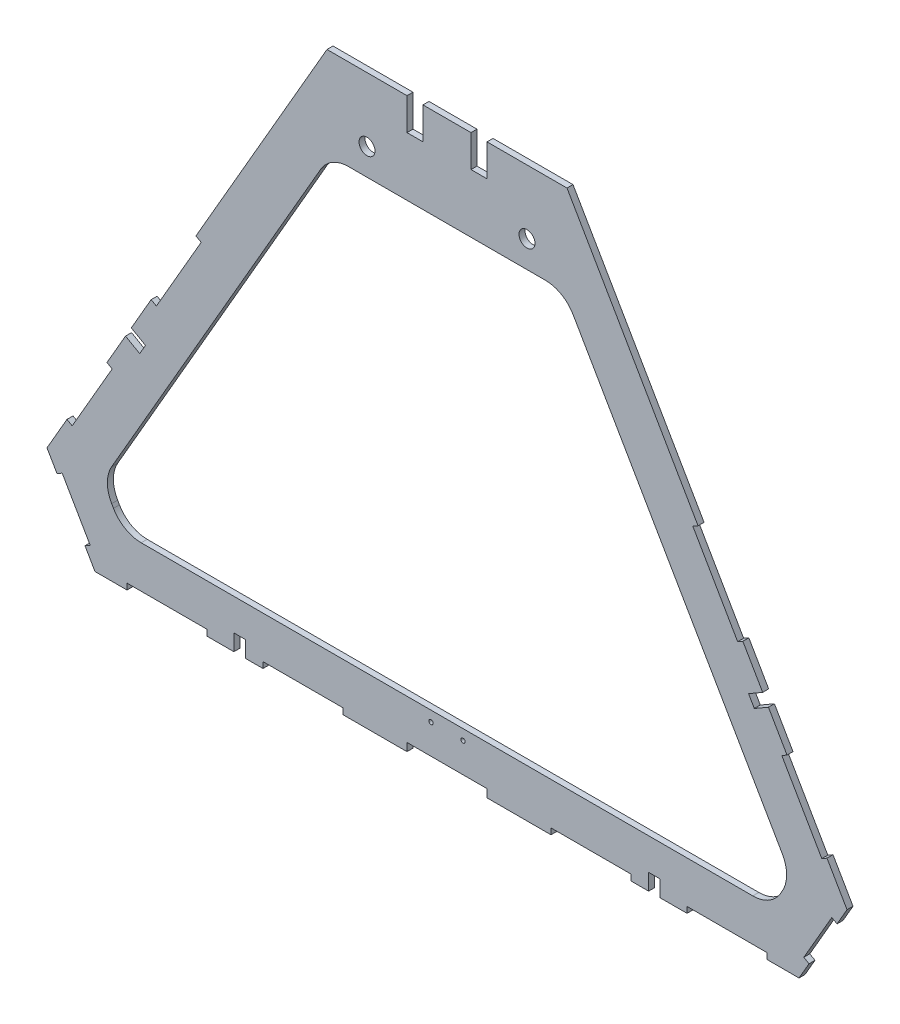
SolidWorks part; units mm, degrees
material "Balsa"
ref_plane "Front Plane" through (0, 0, 0) normal (0, 0, 1) x (1, 0, 0)
ref_plane "Top Plane" through (0, 0, 0) normal (0, 1, 0) x (1, 0, 0)
ref_plane "Right Plane" through (0, 0, 0) normal (1, 0, 0) x (0, 0, -1)
sketch "Sketch1" plane through (0, 0, 0) normal (0, 0, 1) x (1, 0, 0)
  line L0 (-95.25, 450.9394) -> (95.25, 450.9394)
  line L1 (317.5, 65.9911) -> (95.25, 450.9394)
  line L2 (-95.25, 450.9394) -> (-317.5, 65.9911)
  line L3 (-317.5, 65.9911) -> (-279.4, 0)
  line L4 (-279.4, 0) -> (279.4, 0)
  line L5 (279.4, 0) -> (317.5, 65.9911)
  line L6 (0, 0) -> (0, -278.1082) construction
  line L7 (0, 0) -> (435.0174, 0) construction
  point P5 (0, 0)
  point P7 (0, 450.9394)
  dimension "D1" = 558.8
  dimension "D2" = 76.2
  dimension "D3" = 60
  dimension "D4" = 60
  dimension "D5" = 444.5
  dimension "D6" = 60
extrude "Boss-Extrude2" add sketch "Sketch1" along normal blind 4.7625
sketch "Sketch2" plane through (0, 0, 4.7625) normal (0, 0, 1) x (1, 0, 0)
  line L11 (-92.8086, 378.968) -> (92.8086, 378.968)
  line L12 (-279.4, 0) -> (279.4, 0) construction
  line L17 (257.403, 38.1) -> (273.5059, 65.9911)
  line L18 (273.5059, 65.9911) -> (73.253, 412.8394)
  line L19 (73.253, 412.8394) -> (-73.253, 412.8394)
  line L20 (-73.253, 412.8394) -> (-273.5059, 65.9911)
  line L21 (-273.5059, 65.9911) -> (-257.403, 38.1)
  line L25 (-257.403, 38.1) -> (257.403, 38.1)
  line L26 (257.403, 38.1) -> (273.5059, 65.9911)
  line L27 (273.5059, 65.9911) -> (92.8086, 378.968)
  line L29 (-92.8086, 378.968) -> (-273.5059, 65.9911)
  line L30 (-273.5059, 65.9911) -> (-257.403, 38.1)
  line L31 (-257.403, 38.1) -> (257.403, 38.1)
  dimension "D2" = 378.968
  dimension "D1" = 38.1
extrude "Cut-Extrude1" cut sketch "Sketch2" against normal up to next
fillet "Fillet1" radius 25.4 6 edges at (273.5059, 65.9911, 2.3813) (257.403, 38.1, 2.3813) (-257.403, 38.1, 2.3813) (-273.5059, 65.9911, 2.3813) (92.8086, 378.968, 2.3813) (-92.8086, 378.968, 2.3813)
sketch "Sketch3" plane through (0, 0, 4.7625) normal (0, 0, 1) x (1, 0, 0)
  line L0 (0, 450.9394) -> (0, 0) construction
  line L1 (95.25, 450.9394) -> (-95.25, 450.9394) construction
  line L2 (-279.4, 0) -> (279.4, 0) construction
  line L3 (-254, 0) -> (-190.5, 0)
  line L4 (-190.5, 0) -> (-190.5, 4.7625)
  line L5 (-190.5, 4.7625) -> (-254, 4.7625)
  line L6 (-254, 4.7625) -> (-254, 0)
  line L7 (-146.05, 0) -> (-146.05, 4.7625)
  line L8 (-146.05, 4.7625) -> (-82.55, 4.7625)
  line L9 (-82.55, 4.7625) -> (-82.55, 0)
  line L10 (-82.55, 0) -> (-146.05, 0)
  line L11 (-31.75, 0) -> (-31.75, 6.35)
  line L12 (-31.75, 6.35) -> (31.75, 6.35)
  line L14 (31.75, 0) -> (-31.75, 0)
  line L24 (31.75, 0) -> (31.75, 6.35)
  line L33 (-95.25, 450.9394) -> (-317.5, 65.9911) construction
  line L37 (-199.263, 270.7836) -> (-195.1386, 268.4024)
  line L38 (-195.1386, 268.4024) -> (-230.6986, 206.8107)
  line L39 (-230.6986, 206.8107) -> (-234.823, 209.1919)
  line L40 (-234.823, 209.1919) -> (-199.263, 270.7836)
  line L41 (-269.875, 148.4801) -> (-265.7506, 146.0988)
  line L42 (-265.7506, 146.0988) -> (-297.5006, 91.1062)
  line L43 (-297.5006, 91.1062) -> (-301.625, 93.4874)
  line L44 (-301.625, 93.4874) -> (-269.875, 148.4801)
  line L45 (-309.5625, 52.243) -> (-305.4381, 54.6242)
  line L46 (-317.5, 65.9911) -> (-279.4, 0) construction
  line L47 (-305.4381, 54.6242) -> (-283.2131, 16.1294)
  line L48 (-283.2131, 16.1294) -> (-287.3375, 13.7482)
  line L49 (-287.3375, 13.7482) -> (-309.5625, 52.243)
  line L50 (287.3375, 13.7482) -> (309.5625, 52.243)
  line L51 (283.2131, 16.1294) -> (287.3375, 13.7482)
  line L52 (305.4381, 54.6242) -> (283.2131, 16.1294)
  line L53 (309.5625, 52.243) -> (305.4381, 54.6242)
  line L54 (301.625, 93.4874) -> (269.875, 148.4801)
  line L55 (297.5006, 91.1062) -> (301.625, 93.4874)
  line L56 (265.7506, 146.0988) -> (297.5006, 91.1062)
  line L57 (269.875, 148.4801) -> (265.7506, 146.0988)
  line L58 (234.823, 209.1919) -> (199.263, 270.7836)
  line L59 (230.6986, 206.8107) -> (234.823, 209.1919)
  line L60 (195.1386, 268.4024) -> (230.6986, 206.8107)
  line L61 (199.263, 270.7836) -> (195.1386, 268.4024)
  line L62 (82.55, 0) -> (146.05, 0)
  line L63 (82.55, 4.7625) -> (82.55, 0)
  line L64 (146.05, 4.7625) -> (82.55, 4.7625)
  line L65 (146.05, 0) -> (146.05, 4.7625)
  line L66 (254, 4.7625) -> (254, 0)
  line L67 (190.5, 4.7625) -> (254, 4.7625)
  line L68 (190.5, 0) -> (190.5, 4.7625)
  line L69 (254, 0) -> (190.5, 0)
  line L70 (-31.75, 450.9394) -> (-31.75, 425.5394)
  line L71 (-31.75, 425.5394) -> (-19.05, 425.5394)
  line L72 (-19.05, 425.5394) -> (-19.05, 450.9394)
  line L73 (-19.05, 450.9394) -> (-31.75, 450.9394)
  line L74 (19.05, 450.9394) -> (31.75, 450.9394)
  line L75 (19.05, 425.5394) -> (19.05, 450.9394)
  line L76 (31.75, 425.5394) -> (19.05, 425.5394)
  line L77 (31.75, 450.9394) -> (31.75, 425.5394)
  point P16 (-114.3, 0)
  point P45 (0, 6.35)
  point P46 (-222.25, 0)
  point P47 (-285.75, 120.9837)
  point P51 (-217.043, 239.9878)
  dimension "D1" = 31.75
  dimension "D2" = 6.35
  dimension "D3" = 4.7625
  dimension "D4" = 63.5
  dimension "D5" = 114.3
  dimension "D6" = 63.5
  dimension "D7" = 222.25
  dimension "D8" = 44.45
  dimension "D9" = 15.875
  dimension "D10" = 63.5
  dimension "D11" = 63.5
  dimension "D12" = 71.12
  dimension "D13" = 200.914
  dimension "D14" = 12.7
  dimension "D15" = 25.4
  dimension "D16" = 63.5
extrude "Cut-Extrude2" cut sketch "Sketch3" against normal through all
sketch "Sketch4" plane through (0, 0, 4.7625) normal (0, 0, 1) x (1, 0, 0)
  line L0 (0, 450.9394) -> (0, 6.35) construction
  line L1 (19.05, 450.9394) -> (-19.05, 450.9394) construction
  line L2 (31.75, 6.35) -> (-31.75, 6.35) construction
  line L3 (-250.571, 181.9156) -> (-255.143, 173.9966)
  line L4 (-234.823, 209.1919) -> (-269.875, 148.4801) construction
  line L5 (-255.143, 173.9966) -> (-243.9245, 167.5196)
  line L6 (-243.9245, 167.5196) -> (-239.3525, 175.4386)
  line L7 (-239.3525, 175.4386) -> (-250.571, 181.9156)
  line L8 (-169.164, 0) -> (-169.164, 12.954)
  line L9 (-190.5, 0) -> (-146.05, 0) construction
  line L10 (-169.164, 12.954) -> (-160.02, 12.954)
  line L11 (-160.02, 12.954) -> (-160.02, 0)
  line L12 (-160.02, 0) -> (-169.164, 0)
  line L13 (-82.55, 0) -> (-31.75, 0) construction
  line L14 (-63.5, 400.1394) -> (63.5, 400.1394) construction
  line L16 (160.02, 0) -> (169.164, 0)
  line L17 (160.02, 12.954) -> (160.02, 0)
  line L18 (169.164, 12.954) -> (160.02, 12.954)
  line L19 (169.164, 0) -> (169.164, 12.954)
  line L20 (239.3525, 175.4386) -> (250.571, 181.9156)
  line L21 (243.9245, 167.5196) -> (239.3525, 175.4386)
  line L22 (255.143, 173.9966) -> (243.9245, 167.5196)
  line L23 (250.571, 181.9156) -> (255.143, 173.9966)
  circle A0 centre (-12.7, 29.845) radius 1.7145
  circle A1 centre (12.7, 29.845) radius 1.7145
  circle A5 centre (63.5, 400.1394) radius 6.35
  circle A6 centre (-63.5, 400.1394) radius 6.35
  point P21 (-252.857, 177.9561)
  point P22 (-164.592, 0)
  point P40 (0, 400.1394)
  dimension "D5" = 29.845
  dimension "D7" = 3.429
  dimension "D11" = 12.7
  dimension "D1" = 9.144
  dimension "D2" = 12.954
  dimension "D3" = 164.592
  dimension "D4" = 129.286
  dimension "D6" = 12.7
  dimension "D9" = 63.5
  dimension "D10" = 50.8
extrude "Cut-Extrude3" cut sketch "Sketch4" against normal through all
